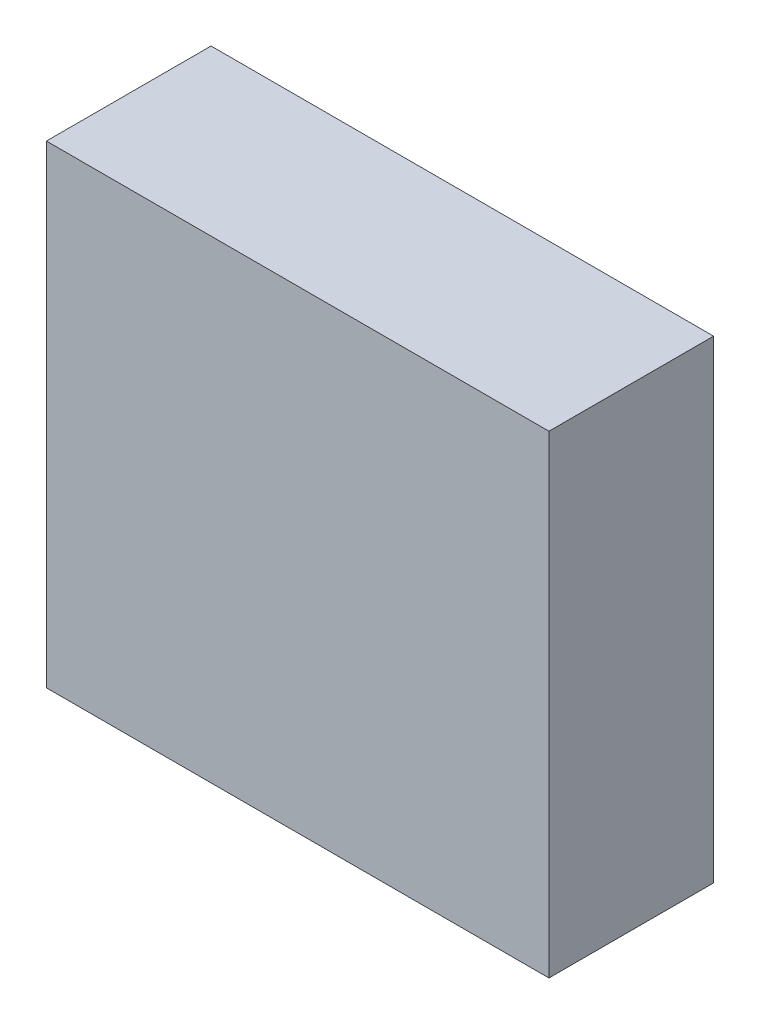
SolidWorks part; units mm, degrees
ref_plane "Front Plane" through (0, 0, 0) normal (0, 0, 1) x (1, 0, 0)
ref_plane "Top Plane" through (0, 0, 0) normal (0, 1, 0) x (1, 0, 0)
ref_plane "Right Plane" through (0, 0, 0) normal (1, 0, 0) x (0, 0, -1)
sketch "Sketch1" plane through (0, 0, 0) normal (0, 0, 1) x (1, 0, 0)
  line L0 (-1.5262, 1.4762) -> (1.5262, 1.4762)
  line L1 (1.5262, 1.4762) -> (1.5262, -1.4)
  line L2 (1.5262, -1.4) -> (-1.5262, -1.4)
  line L3 (-1.5262, -1.4) -> (-1.5262, 1.4762)
extrude "Component_Outline" add sketch "Sketch1" along normal blind 1 separate body
sketch3d "3DSketch1"
  line L0 (0, 0, 0) -> (1, 0, 0)
  line L1 (0, 0, 0) -> (0, 1, 0)
  line L2 (0, 0, 0) -> (0, 0, 1)
  point P0 (0, 0, 0)
